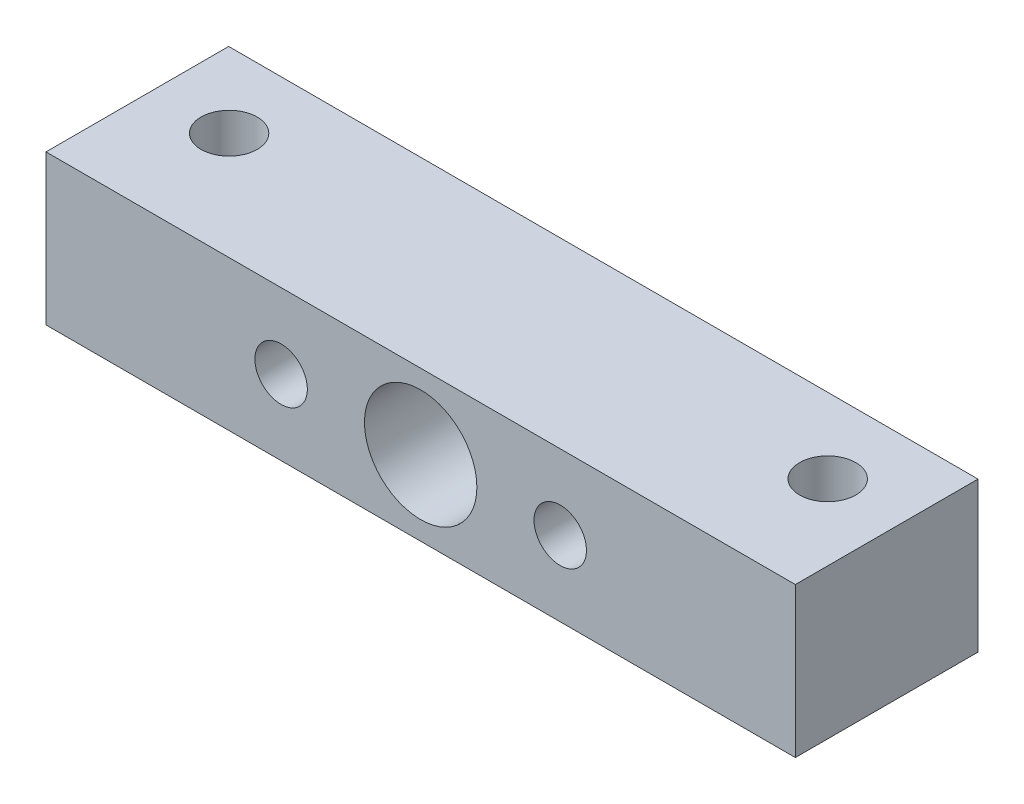
SolidWorks part; units mm, degrees
ref_plane "Front" through (0, 0, 0) normal (0, 0, 1) x (1, 0, 0)
ref_plane "Top" through (0, 0, 0) normal (0, 1, 0) x (1, 0, 0)
ref_plane "Right" through (0, 0, 0) normal (1, 0, 0) x (0, 0, -1)
sketch "Sketch1" plane through (0, 0, 0) normal (0, 1, 0) x (1, 0, 0)
  line L0 (-20, 0) -> (20, 0) construction
  line L1 (20, -4.875) -> (-20, -4.875)
  line L2 (20, -4.875) -> (20, 4.875)
  line L3 (20, 4.875) -> (-20, 4.875)
  line L4 (-20, -4.875) -> (-20, 4.875)
  line L5 (20, -4.875) -> (-20, 4.875) construction
  line L6 (20, 4.875) -> (-20, -4.875) construction
  line L7 (0, 4.875) -> (0, -4.875) construction
  circle A0 centre (-15.9761, 0.875) radius 1.5
  circle A1 centre (15.9761, 0.875) radius 1.5
  point P0 (0, 0)
  dimension "D3" = 3
  dimension "D1" = 40
  dimension "D2" = 9.75
  dimension "D4" = 16
  dimension "D5" = 4
extrude "Boss-Extrude1" add sketch "Sketch1" along normal blind 8
sketch "Sketch2" plane through (0, 0, 4.875) normal (0, 0, 1) x (1, 0, 0)
  line L0 (0, 8) -> (0, 0) construction
  line L1 (-20, 8) -> (20, 8) construction
  line L2 (-20, 0) -> (20, 0) construction
  line L3 (20, 8) -> (20, 0) construction
  circle A0 centre (0, 4) radius 3
  circle A1 centre (8.5, 4.0127) radius 1.5
  circle A2 centre (-8.5, 4.0127) radius 1.5
  point P10 (20, 4)
  dimension "D1" = 6
  dimension "D3" = 3
  dimension "D2" = 11.5
extrude "Cut-Extrude1" cut sketch "Sketch2" against normal up to next contours L0 A0 | A0 L0
sketch "Sketch3" plane through (0, 0, -4.875) normal (0, 0, -1) x (-1, 0, 0)
  line L0 (7.45, 0) -> (7.45, 8) construction
  line L1 (-20, 8) -> (20, 8)
  line L2 (-20, 8) -> (-20, 0)
  line L3 (-20, 0) -> (20, 0)
  line L4 (20, 8) -> (20, 0)
  line L5 (0, 0) -> (0, 8) construction
  line L6 (-20, 4) -> (20, 4) construction
  line L7 (-7.45, 0) -> (-7.45, 8) construction
  circle A1 centre (-7.45, 4) radius 1.4
  circle A2 centre (7.45, 4) radius 1.4
  point P140 (0, 4)
  dimension "D3" = 2.8
  dimension "D4" = 2.8
  dimension "D1" = 7.45
  dimension "D2" = 7.45
extrude "Cut-Extrude2" cut sketch "Sketch3" against normal up to next contours A2 | A1
